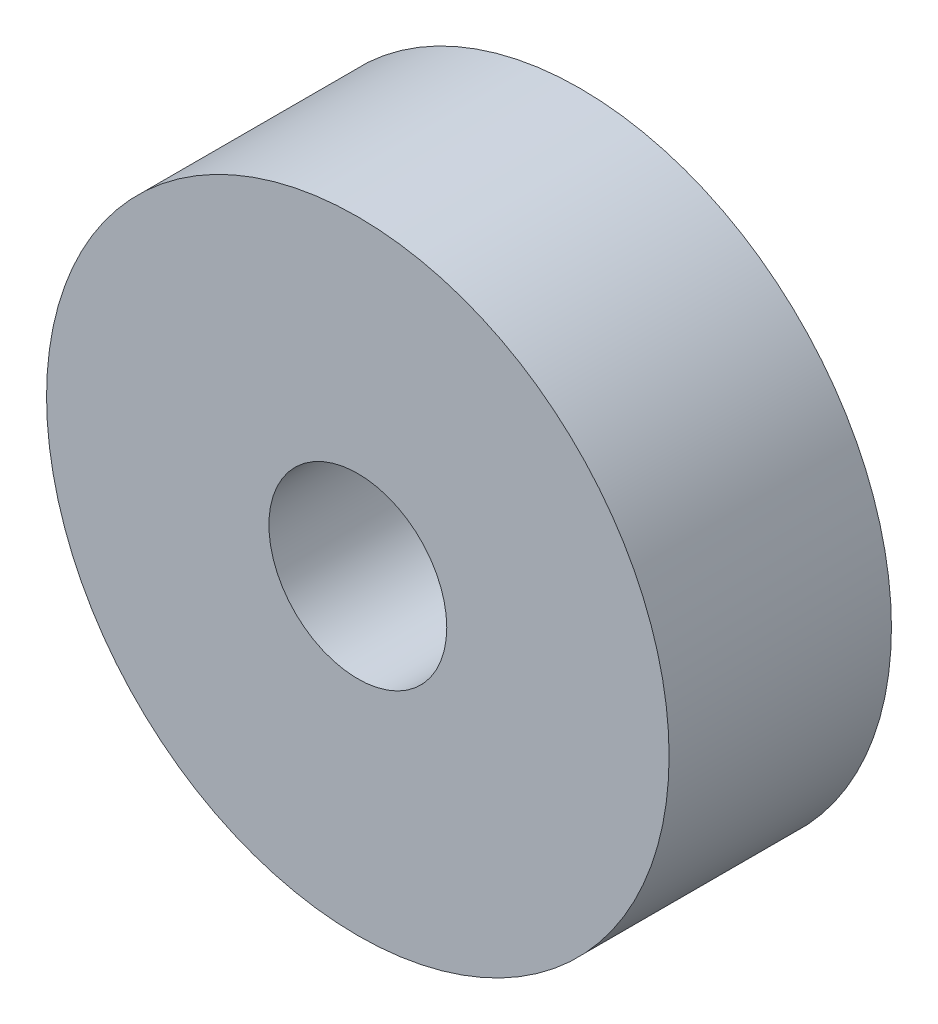
SolidWorks part; units mm, degrees
ref_plane "Front Plane" through (0, 0, 0) normal (0, 0, 1) x (1, 0, 0)
ref_plane "Top Plane" through (0, 0, 0) normal (0, 1, 0) x (1, 0, 0)
ref_plane "Right Plane" through (0, 0, 0) normal (1, 0, 0) x (0, 0, -1)
sketch "Sketch1" plane through (0, 0, 0) normal (0, 0, 1) x (1, 0, 0)
  circle A0 centre (0, 0) radius 4
  circle A1 centre (0, 0) radius 14
  dimension "D1" = 8
  dimension "D2" = 10
extrude "Boss-Extrude1" add sketch "Sketch1" along normal blind 10
